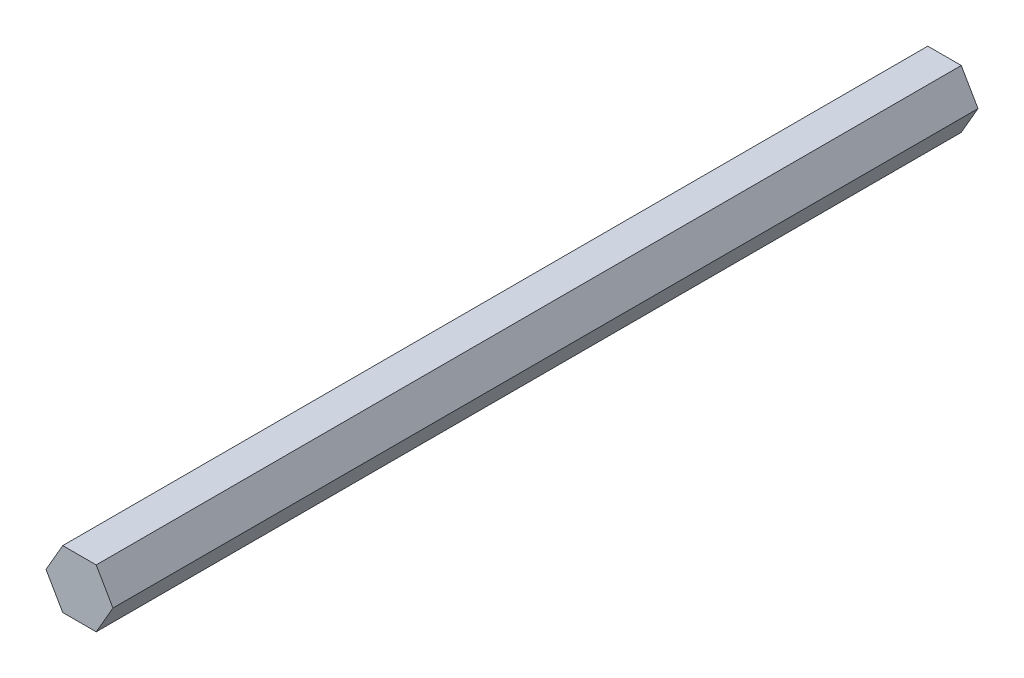
SolidWorks part; units mm, degrees
ref_plane "Alzado" through (0, 0, 0) normal (0, 0, 1) x (1, 0, 0)
ref_plane "Planta" through (0, 0, 0) normal (0, 1, 0) x (1, 0, 0)
ref_plane "Vista lateral" through (0, 0, 0) normal (1, 0, 0) x (0, 0, -1)
sketch "Croquis1" plane through (0, 0, 0) normal (0, 0, 1) x (1, 0, 0)
  line L1 (7.3323, 0) -> (3.6662, 6.35)
  line L2 (3.6662, 6.35) -> (-3.6662, 6.35)
  line L3 (-3.6662, 6.35) -> (-7.3323, 0)
  line L4 (-7.3323, 0) -> (-3.6662, -6.35)
  line L5 (-3.6662, -6.35) -> (3.6662, -6.35)
  line L6 (3.6662, -6.35) -> (7.3323, 0)
  circle A0 centre (0, 0) radius 6.35 construction
  dimension "D1" = 12.7
extrude "Saliente-Extruir1" add sketch "Croquis1" along normal blind 189.5
